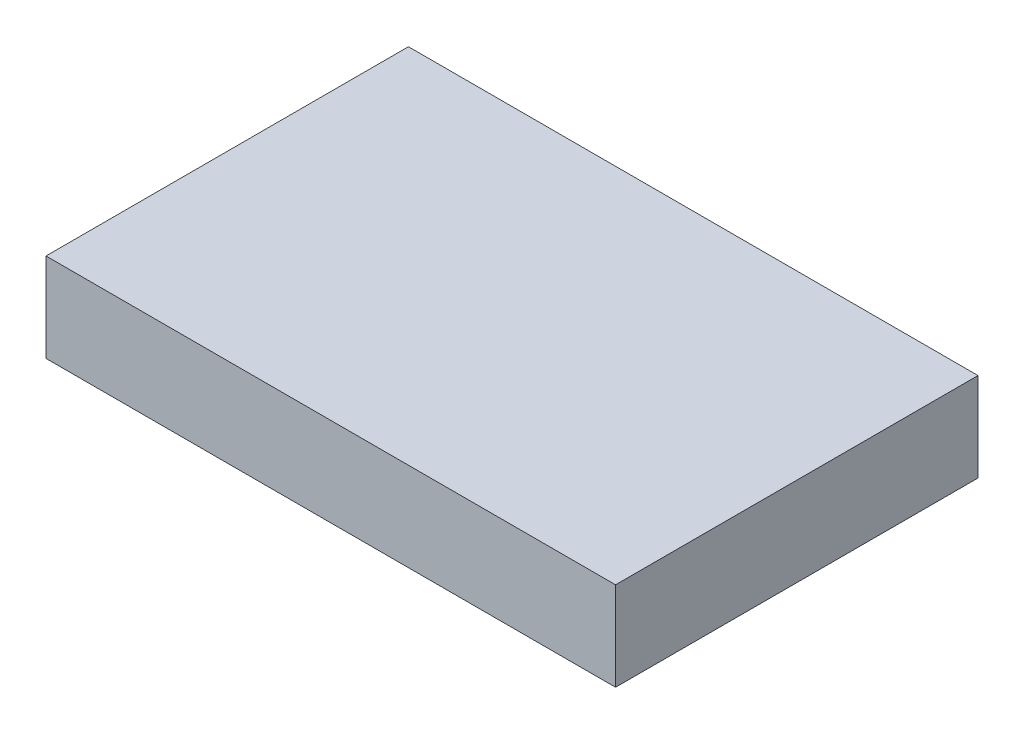
SolidWorks part; units mm, degrees
ref_plane "Plano frontal" through (0, 0, 0) normal (0, 0, 1) x (1, 0, 0)
ref_plane "Plano superior" through (0, 0, 0) normal (0, 1, 0) x (1, 0, 0)
ref_plane "Plano direito" through (0, 0, 0) normal (1, 0, 0) x (0, 0, -1)
sketch "Esboço1" plane through (0, 0, 0) normal (0, 1, 0) x (1, 0, 0)
  line L1 (-38.5, 24.5) -> (38.5, 24.5)
  line L2 (-38.5, 24.5) -> (-38.5, -24.5)
  line L3 (-38.5, -24.5) -> (38.5, -24.5)
  line L4 (38.5, 24.5) -> (38.5, -24.5)
  line L5 (-38.5, 24.5) -> (38.5, -24.5) construction
  line L6 (-38.5, -24.5) -> (38.5, 24.5) construction
  point P0 (0, 0)
  dimension "D1" = 77
  dimension "D2" = 49
extrude "Ressalto-extrusão1" add sketch "Esboço1" along normal blind 12
